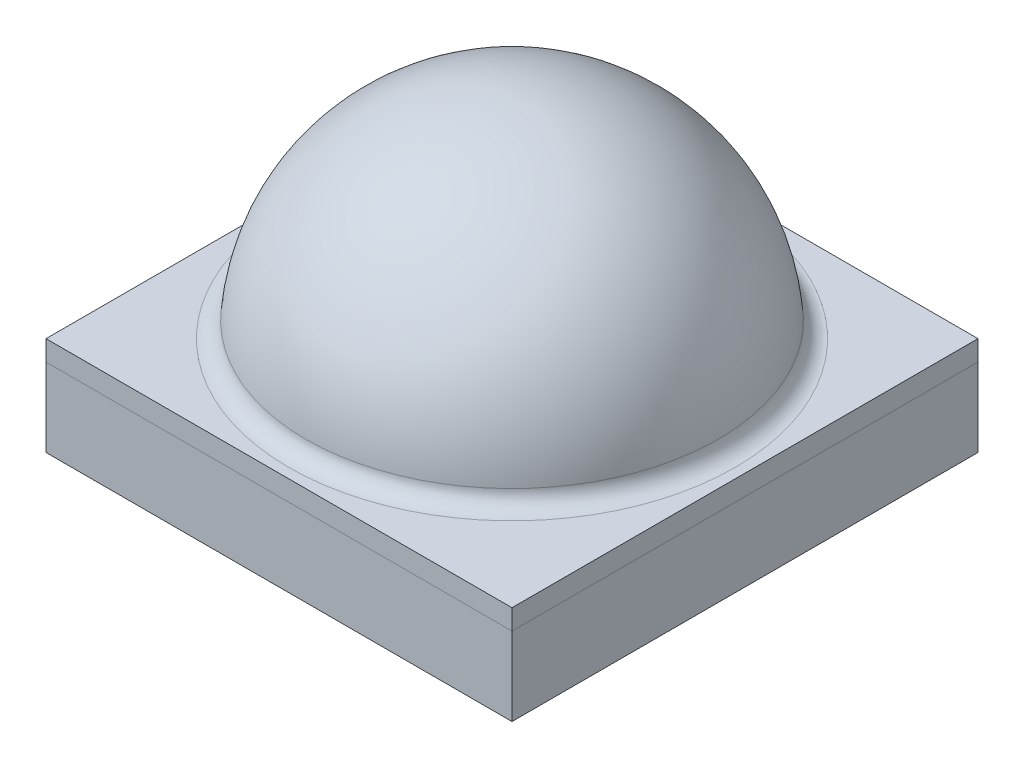
SolidWorks part; units mm, degrees
ref_plane "Front Plane" through (0, 0, 0) normal (0, 0, 1) x (1, 0, 0)
ref_plane "Top Plane" through (0, 0, 0) normal (0, 1, 0) x (1, 0, 0)
ref_plane "Right Plane" through (0, 0, 0) normal (1, 0, 0) x (0, 0, -1)
sketch "Sketch1" plane through (0, 0, 0) normal (0, 1, 0) x (1, 0, 0)
  line L1 (-1.725, 1.725) -> (1.725, 1.725)
  line L2 (-1.725, 1.725) -> (-1.725, -1.725)
  line L3 (-1.725, -1.725) -> (1.725, -1.725)
  line L4 (1.725, 1.725) -> (1.725, -1.725)
  line L5 (-1.725, 1.725) -> (1.725, -1.725) construction
  line L6 (-1.725, -1.725) -> (1.725, 1.725) construction
  point P0 (0, 0)
  dimension "D1" = 3.45
extrude "Boss-Extrude1" add sketch "Sketch1" along normal blind 0.58
sketch "Sketch2" plane through (0, 0.58, 0) normal (0, 1, 0) x (1, 0, 0)
  line L1 (-1.725, 1.725) -> (1.725, 1.725)
  line L2 (-1.725, 1.725) -> (-1.725, -1.725)
  line L3 (-1.725, -1.725) -> (1.725, -1.725)
  line L4 (1.725, 1.725) -> (1.725, -1.725)
  line L5 (-1.725, 1.725) -> (1.725, -1.725) construction
  line L6 (-1.725, -1.725) -> (1.725, 1.725) construction
  point P0 (0, 0)
extrude "Boss-Extrude2" add sketch "Sketch2" along normal blind 0.15 separate body
sketch "Sketch3" plane through (0, 0, 0) normal (1, 0, 0) x (0, 0, -1)
  line L0 (-1.725, 0.73) -> (1.725, 0.73) construction
  line L1 (0, 0.73) -> (1.53, 0.73)
  line L3 (0, 2.26) -> (0, 0.73)
  line L4 (0, 2.26) -> (-0.4254, 2.26) construction
  line L5 (1.53, 0.73) -> (1.53, 0.3562) construction
  arc A0 (0, 2.26) -> (1.53, 0.73) centre (0, 0.73) cw
  dimension "D1" = 1.53
revolve "Revolve1" add sketch "Sketch3" angle 360 about L3
fillet "Fillet1" radius 0.127 1 edges at (0, 0.73, 1.53)
